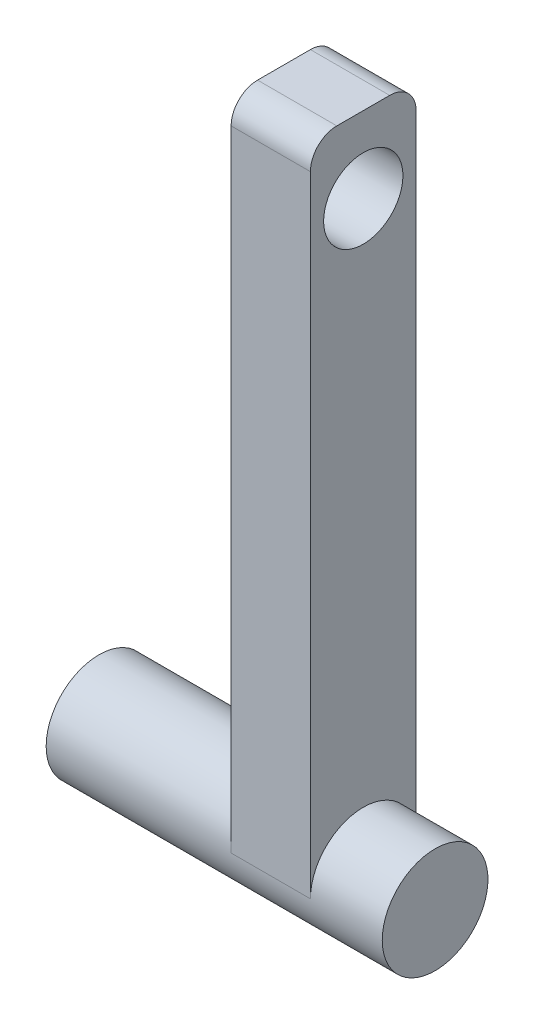
SolidWorks part; units mm, degrees
ref_plane "Front Plane" through (0, 0, 0) normal (0, 0, 1) x (1, 0, 0)
ref_plane "Top Plane" through (0, 0, 0) normal (0, 1, 0) x (1, 0, 0)
ref_plane "Right Plane" through (0, 0, 0) normal (1, 0, 0) x (0, 0, -1)
sketch "Sketch1" plane through (0, 0, 0) normal (1, 0, 0) x (0, 0, -1)
  circle A0 centre (-12.6585, 7.0005) radius 2
extrude "Boss-Extrude1" add sketch "Sketch1" along normal blind 42
sketch "Sketch2" plane through (0, 0, 0) normal (-1, 0, 0) x (0, 0, 1)
  line L0 (10.6585, 7.0005) -> (10.6585, 13.7605)
  line L1 (14.6585, 13.7605) -> (14.6585, 7.0005)
  circle A0 centre (12.6585, 7.0005) radius 2 construction
  arc A1 (10.6585, 13.7605) -> (14.6585, 13.7605) centre (12.6585, 13.7605) cw
  circle A3 centre (12.6585, 7.0005) radius 2
  arc A4 (10.6585, 7.0005) -> (14.6585, 7.0005) centre (12.6585, 7.0005) ccw
  dimension "D1" = 0
extrude "Boss-Extrude2" add sketch "Sketch2" against normal blind 10
sketch "Sketch3" plane through (0, 0, 0) normal (-1, 0, 0) x (0, 0, 1)
  line L0 (10.6585, 7.0005) -> (10.6585, 13.7605)
  line L1 (14.6585, 13.7605) -> (14.6585, 7.0005)
  arc A0 (14.6585, 7.0005) -> (10.6585, 7.0005) centre (12.6585, 7.0005) ccw
  arc A1 (10.6585, 7.0005) -> (14.6585, 7.0005) centre (12.6585, 7.0005) ccw construction
  arc A3 (14.6585, 13.7605) -> (10.6585, 13.7605) centre (12.6585, 13.7605) ccw construction
  arc A4 (14.6585, 13.7605) -> (10.6585, 13.7605) centre (12.6585, 13.7605) ccw
extrude "Cut-Extrude1" cut sketch "Sketch3" against normal blind 7
sketch "Sketch4" plane through (7, 0, 0) normal (-1, 0, 0) x (0, 0, 1)
  line L0 (10.6585, 7.0005) -> (10.6585, 13.7605)
  line L1 (10.6585, 13.7605) -> (10.6585, 36.0099)
  line L2 (14.6585, 36.0099) -> (14.6585, 7.0005)
  line L3 (10.6585, 36.0099) -> (14.6585, 36.0099)
  arc A0 (10.6585, 36.0099) -> (14.6585, 36.0099) centre (12.6585, 36.0099) cw
  arc M3 (14.6585, 13.7605) -> (10.6585, 13.7605) centre (12.6585, 13.7605) ccw
extrude "Boss-Extrude4" add sketch "Sketch4" against normal blind 3 contours L3 L1 L2 M3 | A0 L3
sketch "Sketch5" plane through (7, 0, 0) normal (-1, 0, 0) x (0, 0, 1)
  line L0 (10.6585, 22.9195) -> (14.6585, 22.9195) construction
  line L1 (10.6585, 36.0099) -> (10.6585, 7.0005) construction
  line L2 (14.6585, 7.0005) -> (14.6585, 36.0099) construction
  circle A0 centre (12.7066, 22.9195) radius 1.5
extrude "Cut-Extrude3" cut sketch "Sketch5" against normal through all contours A0
sketch "Sketch6" plane through (7, 0, 0) normal (-1, 0, 0) x (0, 0, 1)
  line L1 (18.5418, 38.6954) -> (6.7193, 38.6954)
  line L2 (18.5418, 38.6954) -> (18.5418, 26.5383)
  line L3 (18.5418, 26.5383) -> (6.7193, 26.5383)
  line L4 (6.7193, 38.6954) -> (6.7193, 26.5383)
extrude "Cut-Extrude5" cut sketch "Sketch6" against normal through all
fillet "Fillet4" radius 1 1 edges at (8.5, 26.5383, 14.6585)
fillet "Fillet5" radius 1 1 edges at (8.5, 26.5383, 10.6585)
sketch "Sketch7" plane through (0, 0, 10.6585) normal (0, 0, -1) x (-1, 0, 0)
  line L1 (-47.2323, 13.7255) -> (-12.7187, 13.7255)
  line L2 (-47.2323, 13.7255) -> (-47.2323, -0.9974)
  line L3 (-47.2323, -0.9974) -> (-12.7187, -0.9974)
  line L4 (-12.7187, 13.7255) -> (-12.7187, -0.9974)
extrude "Cut-Extrude6" cut sketch "Sketch7" against normal through all
sketch "Sketch8" plane through (7, 0, 0) normal (-1, 0, 0) x (0, 0, 1)
  line L0 (10.6585, 25.5383) -> (10.6585, 7.0005) construction
  line L1 (10.6585, 31.8319) -> (14.6585, 31.8319)
  line L2 (10.6585, 31.8319) -> (10.6585, 19.0234)
  line L3 (10.6585, 19.0234) -> (14.6585, 19.0234)
  line L4 (14.6585, 31.8319) -> (14.6585, 19.0234)
  line L5 (14.6585, 7.0005) -> (14.6585, 25.5383) construction
  line L6 (12.6585, 31.8319) -> (12.6585, 26.9273) construction
  circle A1 centre (12.6585, 28.954) radius 1.5
extrude "Boss-Extrude5" add sketch "Sketch8" against normal up to surface (3 mm away) contours A1 | L2 L1 L4 L3
fillet "Fillet6" radius 1 2 edges at (8.5, 31.8319, 14.6585) (8.5, 31.8319, 10.6585)
